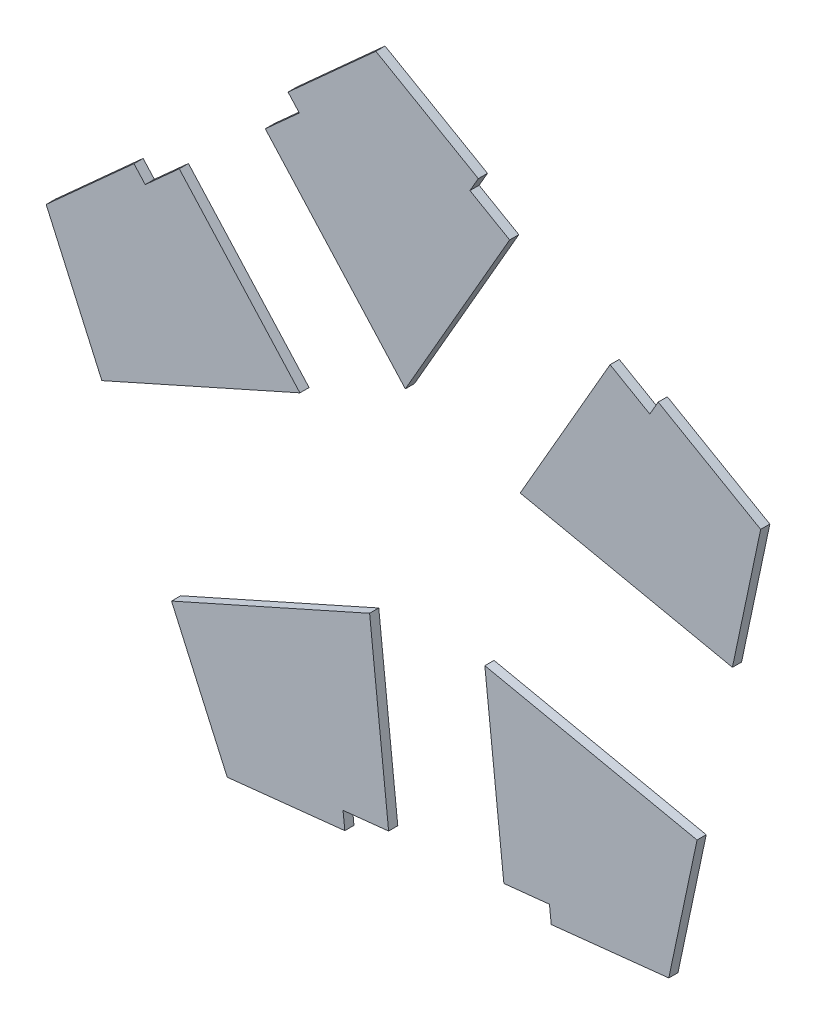
SolidWorks part; units mm, degrees
ref_plane "Front Plane" through (0, 0, 0) normal (0, 0, 1) x (1, 0, 0)
ref_plane "Top Plane" through (0, 0, 0) normal (0, 1, 0) x (1, 0, 0)
ref_plane "Right Plane" through (0, 0, 0) normal (1, 0, 0) x (0, 0, -1)
sketch "Sketch14" plane through (0, 0, 0) normal (0, 0, 1) x (1, 0, 0)
  line L0 (-77.3852, 57.4568) -> (-37.8995, 13.6984)
  line L1 (-13.0529, 122.9157) -> (-3.4064, 32.0772) construction
  line L2 (17.7329, 98.8388) -> (20.4777, 103.6049)
  line L3 (-37.8995, 13.6984) -> (-102.7107, -15.2411)
  line L4 (-102.7107, -15.2411) -> (-120.9333, 25.569)
  line L5 (-120.9333, 25.569) -> (-92.2062, 51.4912)
  line L6 (20.4777, 103.6049) -> (-13.0529, 122.9157)
  line L7 (30.7313, 91.3528) -> (17.7329, 98.8388)
  line L8 (-92.2062, 51.4912) -> (-88.5215, 47.4078)
  line L9 (-88.5215, 47.4078) -> (-77.3852, 57.4568)
  line L10 (-79.9106, -66.303) -> (-61.688, -107.1132)
  line L11 (-61.688, -107.1132) -> (-23.2106, -103.0271)
  line L12 (-23.2106, -103.0271) -> (-23.7914, -97.5578)
  line L13 (-23.7914, -97.5578) -> (-8.8753, -95.9738)
  line L14 (-3.4064, 32.0772) -> (30.7313, 91.3528)
  line L15 (79.3356, 69.7078) -> (76.5907, 64.9417)
  line L16 (-8.8753, -95.9738) -> (-15.0994, -37.3635)
  line L17 (112.8662, 50.3971) -> (79.3356, 69.7078)
  line L18 (-15.0994, -37.3635) -> (-79.9106, -66.303)
  line L26 (103.6209, 6.67) -> (112.8662, 50.3971)
  line L28 (-3.4064, 32.0772) -> (-49.2317, 82.8612)
  line L29 (34.1773, 21.3525) -> (103.6209, 6.67)
  line L30 (63.5923, 72.4277) -> (34.1773, 21.3525)
  line L31 (-49.2317, 82.8612) -> (-38.0954, 92.9102)
  line L32 (-38.0954, 92.9102) -> (-41.78, 96.9935)
  line L33 (-41.78, 96.9935) -> (-13.0529, 122.9157)
  line L35 (76.5907, 64.9417) -> (63.5923, 72.4277)
  line L38 (28.8337, -91.9694) -> (22.6096, -33.359)
  line L39 (43.7498, -90.3854) -> (28.8337, -91.9694)
  line L41 (44.3306, -95.8546) -> (43.7498, -90.3854)
  line L42 (82.808, -91.7686) -> (44.3306, -95.8546)
  line L43 (92.0533, -48.0415) -> (82.808, -91.7686)
  line L44 (22.6096, -33.359) -> (92.0533, -48.0415)
extrude "Boss-Extrude1" add sketch "Sketch14" along normal blind 3
